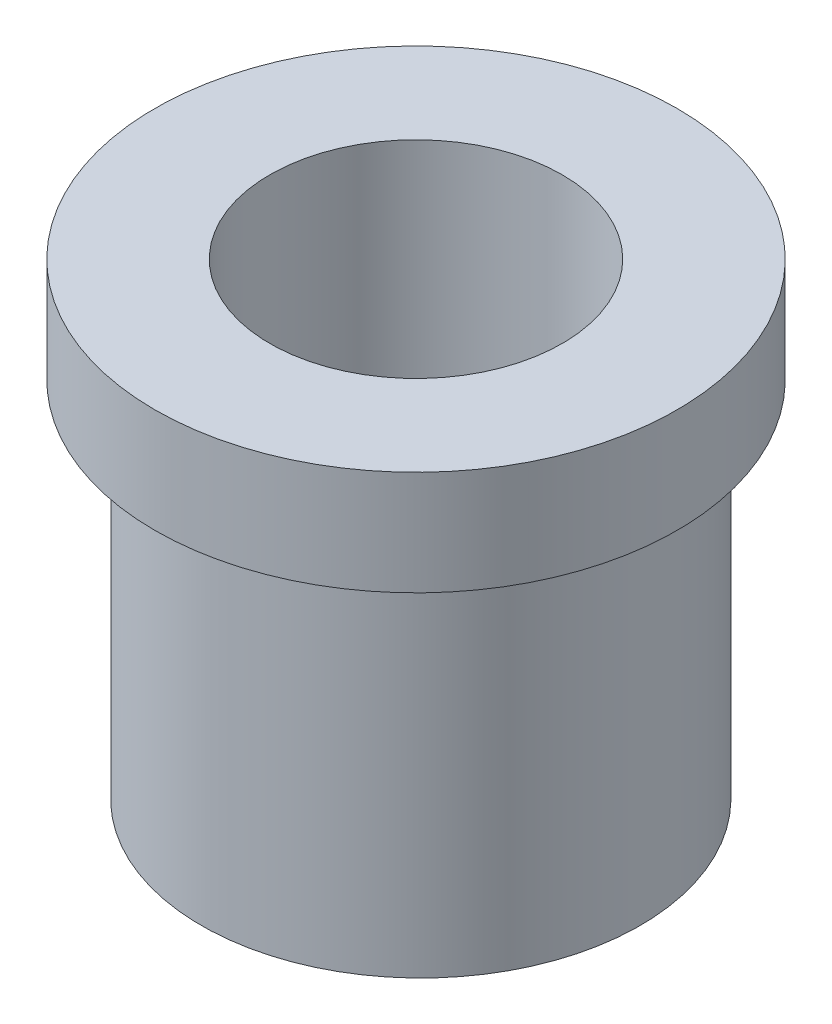
SolidWorks part; units mm, degrees
ref_plane "前视基准面" through (0, 0, 0) normal (0, 0, 1) x (1, 0, 0)
ref_plane "上视基准面" through (0, 0, 0) normal (0, 1, 0) x (1, 0, 0)
ref_plane "右视基准面" through (0, 0, 0) normal (1, 0, 0) x (0, 0, -1)
sketch "草图1" plane through (0, 0, 0) normal (0, 1, 0) x (1, 0, 0)
  circle A0 centre (0, 0) radius 14
  circle A1 centre (0, 0.4552) radius 21
extrude "凸台-拉伸1" add sketch "草图1" along normal blind 45
sketch "草图2" plane through (0, 45, 0) normal (0, 1, 0) x (1, 0, 0)
  circle A0 centre (0, 0) radius 25
  circle A1 centre (0, 0) radius 14
extrude "凸台-拉伸2" add sketch "草图2" against normal blind 10
